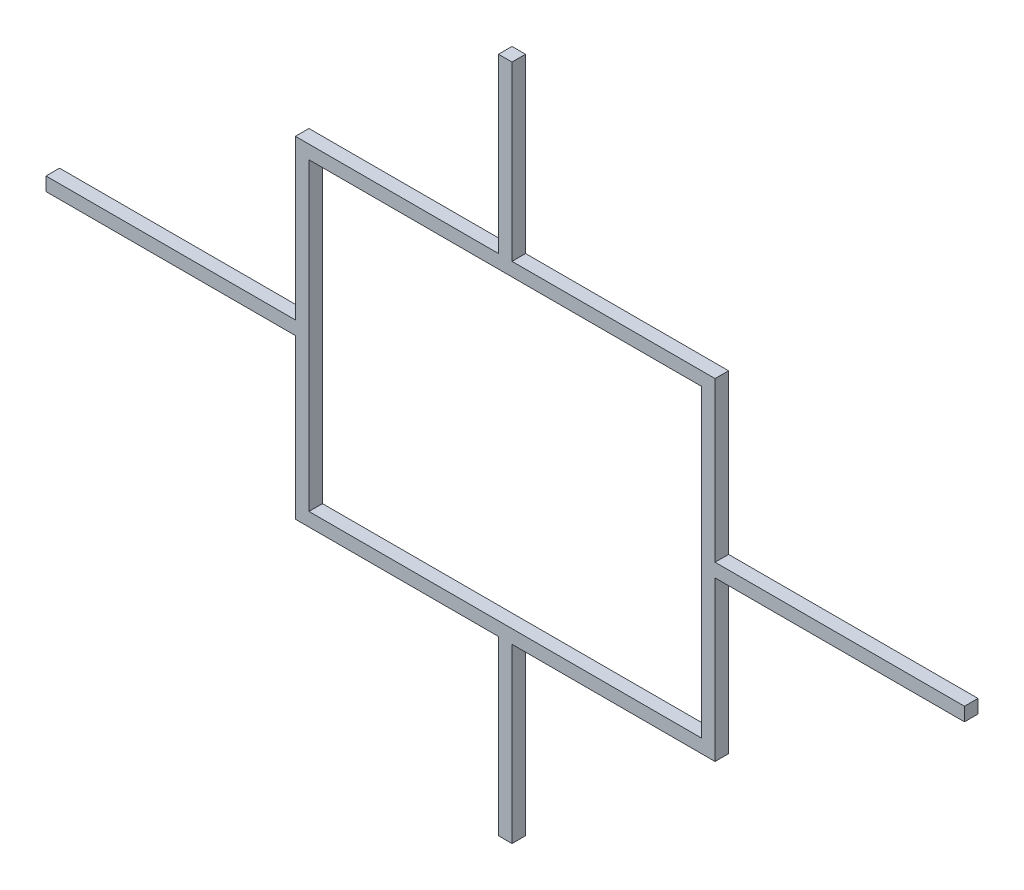
SolidWorks part; units mm, degrees
ref_plane "Front Plane" through (0, 0, 0) normal (0, 0, 1) x (1, 0, 0)
ref_plane "Top Plane" through (0, 0, 0) normal (0, 1, 0) x (1, 0, 0)
ref_plane "Right Plane" through (0, 0, 0) normal (1, 0, 0) x (0, 0, -1)
sketch "Sketch1" plane through (0, 0, 0) normal (0, 0, 1) x (1, 0, 0)
  line L0 (0, 0) -> (0, 1000) construction
  line L1 (0, 1000) -> (1357, 1000) construction
  line L2 (1357, 1000) -> (1357, 0) construction
  line L3 (1357, 0) -> (0, 0) construction
  line L6 (368.5, 745) -> (668.5, 745)
  line L7 (388.5, 725) -> (968.5, 725)
  line L8 (388.5, 725) -> (388.5, 275)
  line L9 (388.5, 275) -> (968.5, 275)
  line L10 (968.5, 725) -> (968.5, 275)
  line L13 (988.5, 745) -> (988.5, 510)
  line L14 (368.5, 255) -> (668.5, 255)
  line L15 (368.5, 745) -> (368.5, 510)
  line L16 (688.5, 0) -> (668.5, 0)
  line L18 (688.5, 745) -> (688.5, 1000)
  line L19 (688.5, 1000) -> (668.5, 1000)
  line L20 (668.5, 745) -> (668.5, 1000)
  line L21 (668.5, 255) -> (668.5, 0)
  line L22 (688.5, 255) -> (688.5, 0)
  line L23 (988.5, 510) -> (1357, 510)
  line L24 (1357, 510) -> (1357, 490)
  line L25 (1357, 490) -> (988.5, 490)
  line L26 (0, 490) -> (368.5, 490)
  line L27 (0, 510) -> (0, 490)
  line L28 (368.5, 510) -> (0, 510)
  line L29 (688.5, 745) -> (988.5, 745)
  line L30 (368.5, 745) -> (988.5, 745) construction
  line L32 (988.5, 490) -> (988.5, 255)
  line L33 (988.5, 745) -> (988.5, 255) construction
  line L34 (688.5, 255) -> (988.5, 255)
  line L35 (368.5, 255) -> (988.5, 255) construction
  line L36 (368.5, 490) -> (368.5, 255)
  line L37 (368.5, 745) -> (368.5, 255) construction
  point P9 (678.5, 500)
  dimension "D1" = 1357
  dimension "D2" = 1000
  dimension "D3" = 450
  dimension "D4" = 580
  dimension "D7" = 20
  dimension "D9" = 20
  dimension "D5" = 20
extrude "Boss-Extrude1" add sketch "Sketch1" along normal blind 20
